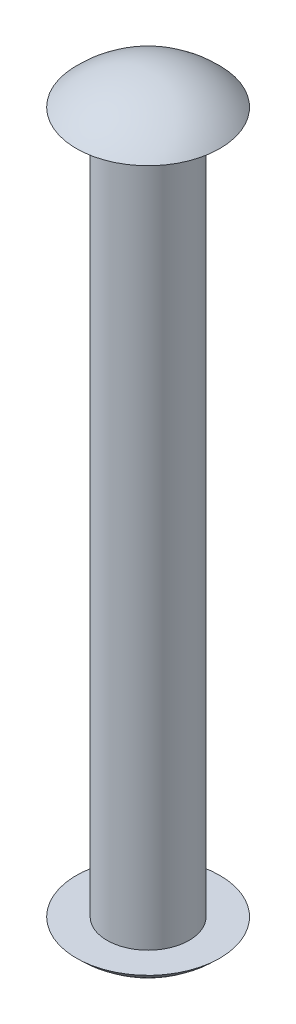
SolidWorks part; units mm, degrees
material "Plain Carbon Steel"
ref_plane "Front Plane" through (0, 0, 0) normal (0, 0, 1) x (1, 0, 0)
ref_plane "Top Plane" through (0, 0, 0) normal (0, 1, 0) x (1, 0, 0)
ref_plane "Right Plane" through (0, 0, 0) normal (1, 0, 0) x (0, 0, -1)
sketch "Sketch1" plane through (0, 0, 0) normal (0, 0, 1) x (1, 0, 0)
  line L0 (2.54, -21.717) -> (2.54, 21.717)
  line L1 (2.54, 21.717) -> (4.445, 21.717)
  line L2 (0, 0) -> (0, 32.1416) construction
  line L3 (0, 23.622) -> (0, -23.622)
  line L4 (4.8895, 0) -> (-4.8895, 0) construction
  line L5 (2.54, -21.717) -> (4.445, -21.717)
  arc A0 (4.445, 21.717) -> (0, 23.622) centre (0, 17.4837) ccw
  arc A1 (4.445, -21.717) -> (0, -23.622) centre (0, -17.4837) cw
  point P14 (2.54, 0)
  dimension "D4" = 1.905
  dimension "D1" = 2.54
  dimension "D2" = 43.434
  dimension "D3" = 4.445
revolve "Revolve1" add sketch "Sketch1" angle 360 about L2
